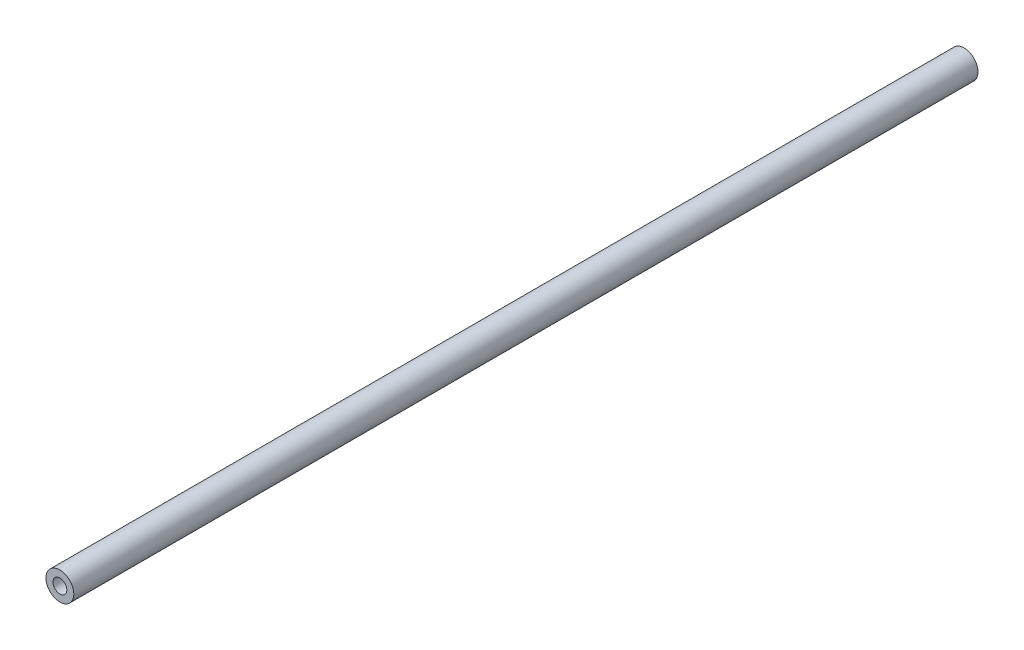
SolidWorks part; units mm, degrees
ref_plane "前视基准面" through (0, 0, 0) normal (0, 0, 1) x (1, 0, 0)
ref_plane "上视基准面" through (0, 0, 0) normal (0, 1, 0) x (1, 0, 0)
ref_plane "右视基准面" through (0, 0, 0) normal (1, 0, 0) x (0, 0, -1)
sketch "草图1" plane through (0, 0, 0) normal (0, 0, 1) x (1, 0, 0)
  circle A0 centre (0, 0) radius 4
extrude "凸台-拉伸1" add sketch "草图1" along normal blind 260
sketch "草图2" plane through (0, 0, 260) normal (0, 0, 1) x (1, 0, 0)
  circle A0 centre (0, 0) radius 2
  dimension "D1" = 4
extrude "切除-拉伸1" cut sketch "草图2" against normal blind 10
sketch "草图3" plane through (0, 0, 0) normal (0, 0, -1) x (-1, 0, 0)
  circle A0 centre (0, 0) radius 2
  dimension "D1" = 4
extrude "切除-拉伸2" cut sketch "草图3" against normal blind 10
